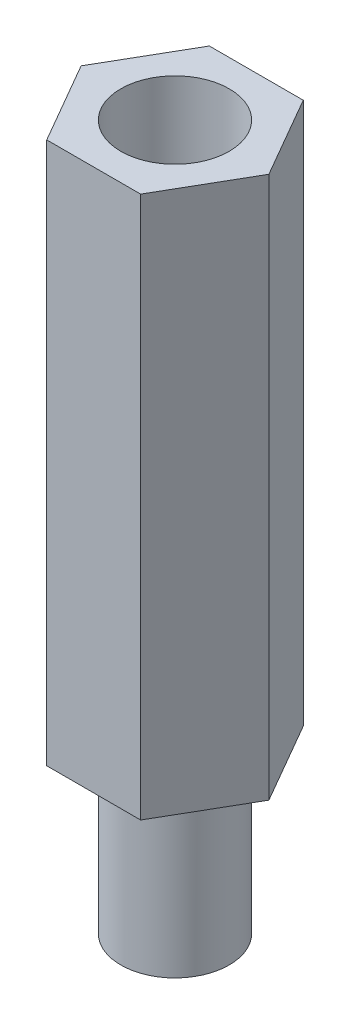
SolidWorks part; units mm, degrees
ref_plane "前视基准面" through (0, 0, 0) normal (0, 0, 1) x (1, 0, 0)
ref_plane "上视基准面" through (0, 0, 0) normal (0, 1, 0) x (1, 0, 0)
ref_plane "右视基准面" through (0, 0, 0) normal (1, 0, 0) x (0, 0, -1)
sketch "草图1" plane through (0, 0, 0) normal (0, 1, 0) x (1, 0, 0)
  line L1 (3.4641, 0) -> (1.7321, 3)
  line L2 (1.7321, 3) -> (-1.7321, 3)
  line L3 (-1.7321, 3) -> (-3.4641, 0)
  line L4 (-3.4641, 0) -> (-1.7321, -3)
  line L5 (-1.7321, -3) -> (1.7321, -3)
  line L6 (1.7321, -3) -> (3.4641, 0)
  circle A0 centre (0, 0) radius 3 construction
  circle A1 centre (0, 0) radius 2
  dimension "D1" = 6
  dimension "D2" = 4
extrude "凸台-拉伸1" add sketch "草图1" along normal blind 20
sketch "草图2" plane through (0, 0, 0) normal (0, -1, 0) x (1, 0, 0)
  circle A0 centre (0, 0) radius 2
extrude "凸台-拉伸2" add sketch "草图2" along normal blind 6 and the other way blind 5
